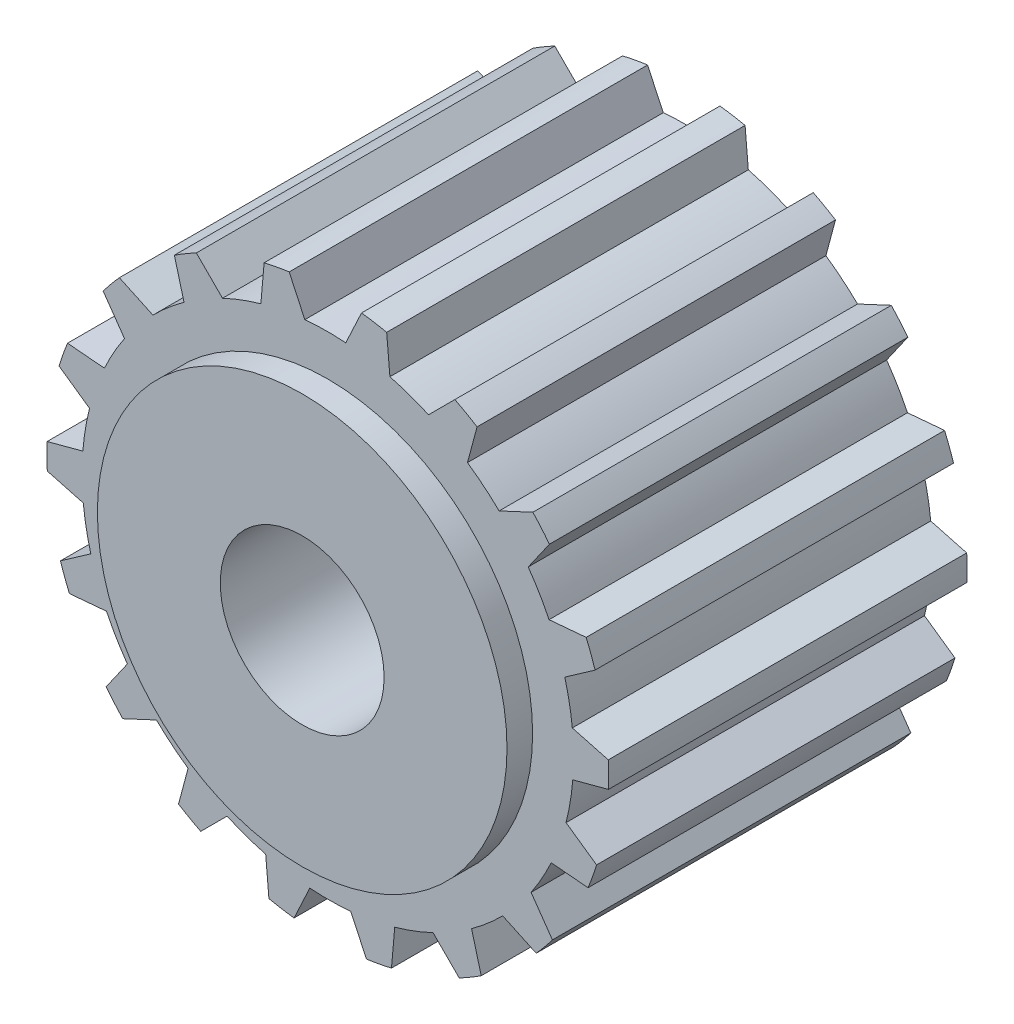
SolidWorks part; units mm, degrees
ref_plane "Face" through (0, 0, 0) normal (0, 0, 1) x (1, 0, 0)
ref_plane "Dessus" through (0, 0, 0) normal (0, 1, 0) x (1, 0, 0)
ref_plane "Droite" through (0, 0, 0) normal (1, 0, 0) x (0, 0, -1)
sketch "Esquisse1" plane through (0, 0, 0) normal (0, 0, 1) x (1, 0, 0)
  line L0 (0, 0) -> (0, 69.2099) construction
  circle A0 centre (0, 0) radius 4
  circle A1 centre (0, 0) radius 13.715
  dimension "D1" = 27.43
  dimension "D2" = 8
extrude "Base-Extrusion" add sketch "Esquisse1" along normal mid plane 20
sketch "Esquisse9" plane through (0, 0, 0) normal (1, 0, 0) x (0, 0, -1)
  line L0 (-10, 13.715) -> (10, 13.715)
  line L1 (-10, 13.715) -> (10, 13.715)
  line L2 (10, -13.715) -> (-10, -13.715)
  line L3 (10, -13.715) -> (-10, -13.715)
sketch "Esquisse2" plane through (0, 0, 10) normal (0, 0, 1) x (1, 0, 0)
  line L0 (0, 0) -> (-2.3816, 13.5066) construction
  line L1 (0, 0) -> (2.3816, 13.5066) construction
  line L2 (0.8782, 11.9678) -> (1.6467, 13.6158)
  line L3 (-1.1217, 11.9475) -> (-1.8852, 13.5848)
  line L4 (-0.1265, 11.9993) -> (-0.1265, 13.7144) construction
  arc A0 (0.8782, 11.9678) -> (-1.1217, 11.9475) centre (0, 0) ccw
  circle A1 centre (0, 0) radius 13.715 construction
  arc A3 (1.6467, 13.6158) -> (-1.8852, 13.5848) centre (0, 0) ccw
  dimension "D2" = 12
  dimension "D1" = 20
  dimension "D3" = 15
  dimension "D4" = 15
  dimension "D5" = 2
  dimension "D6" = 0.97
extrude "Enlèv. mat.-Extru.1" cut sketch "Esquisse2" against normal through all
pattern_circular "Répétition circulaire1" count 18 every 20 about axis through (0, 0, 0) along (0, 0, 1) of "Enlèv. mat.-Extru.1"
ref_plane "Plan4" through (0, 0, -5) normal (0, 0, 1) x (1, 0, 0)
sketch "Esquisse3" plane through (0, 0, -10) normal (0, 0, -1) x (-1, 0, 0)
  circle A0 centre (0, 0) radius 10
  circle A1 centre (0, 0) radius 13.715
  circle A2 centre (0, 0) radius 13.715 construction
  dimension "D1" = 20
extrude "Enlèv. mat.-Extru.2" cut sketch "Esquisse3" against normal blind 1.25
sketch "Esquisse4" plane through (0, 0, 10) normal (0, 0, 1) x (1, 0, 0)
  circle A0 centre (0, 0) radius 13.715
  circle A1 centre (0, 0) radius 10
  circle A2 centre (0, 0) radius 13.715 construction
  dimension "D1" = 20
extrude "Enlèv. mat.-Extru.3" cut sketch "Esquisse4" against normal blind 1.25
sketch "Esquisse11" plane through (0, 0, 0) normal (1, 0, 0) x (0, 0, -1)
  line L0 (0, 13.715) -> (0, 0) construction
  line L1 (-10, 13.715) -> (10, 13.715) construction
ref_plane "Plan5" through (0, 13.715, 0) normal (0, -1, 0) x (1, 0, 0)
sketch "Esquisse8" plane through (0, 0, 0) normal (1, 0, 0) x (0, 0, -1)
  line L0 (-8.75, 19.4) -> (8.75, 19.4)
  line L1 (0, 0) -> (16.0577, 0) construction
  line L2 (-8.75, 10) -> (-8.75, -10) construction
  line L3 (8.75, -10) -> (8.75, 10) construction
  dimension "D1" = 38.8
surface "Surface-Révolution1" sketch "Esquisse8" parameters "D1"=360
sketch "Esquisse10" plane through (0, 0, 0) normal (1, 0, 0) x (0, 0, -1)
  line L0 (3.4, 4) -> (10, 4)
  line L1 (3.4, 4) -> (10, 4)
  line L2 (-10, 4) -> (-3.4, 4)
  line L3 (-10, 4) -> (-3.4, 4)
  line L4 (10, -4) -> (-10, -4)
  line L5 (10, -4) -> (-10, -4)
